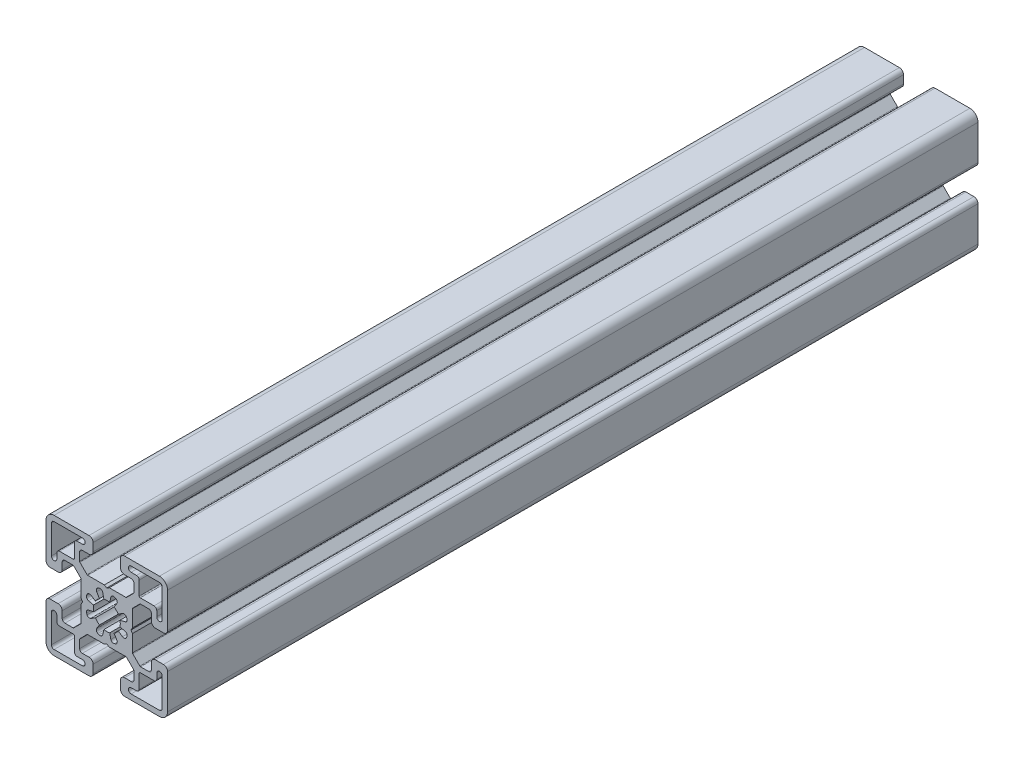
SolidWorks part; units mm, degrees
material "6061 Alloy"
ref_plane "Front Plane" through (0, 0, 0) normal (0, 0, 1) x (1, 0, 0)
ref_plane "Top Plane" through (0, 0, 0) normal (0, 1, 0) x (1, 0, 0)
ref_plane "Right Plane" through (0, 0, 0) normal (1, 0, 0) x (0, 0, -1)
sketch "Sketch1" plane through (0, 0, 0) normal (0, 0, 1) x (1, 0, 0)
  line L0 (-8.0293, -14.4831) -> (-6.0293, -14.4831)
  line L1 (-6.0293, -16.4831) -> (-16.5293, -16.4831)
  line L2 (-17.5293, -15.4831) -> (-17.5293, -4.9831)
  line L3 (-15.5293, -4.9831) -> (-15.5293, -6.9831)
  line L4 (-14.5293, -7.9831) -> (-9.4093, -7.9831)
  line L5 (-9.0293, -8.3631) -> (-9.0293, -13.4831)
  line L6 (-15.5293, 15.0169) -> (-15.5293, 13.0169)
  line L7 (-17.5293, 13.0169) -> (-17.5293, 23.5169)
  line L8 (-16.5293, 24.5169) -> (-6.0293, 24.5169)
  line L9 (-6.0293, 22.5169) -> (-8.0293, 22.5169)
  line L10 (-9.0293, 21.5169) -> (-9.0293, 16.3969)
  line L11 (-9.4093, 16.0169) -> (-14.5293, 16.0169)
  line L12 (14.9707, 16.3969) -> (14.9707, 21.5169)
  line L13 (13.9707, 22.5169) -> (11.9707, 22.5169)
  line L14 (11.9707, 24.5169) -> (22.4707, 24.5169)
  line L15 (23.4707, 23.5169) -> (23.4707, 13.0169)
  line L16 (21.4707, 13.0169) -> (21.4707, 15.0169)
  line L17 (20.4707, 16.0169) -> (15.3507, 16.0169)
  line L18 (8.8137, 0.2931) -> (7.1867, 1.3289)
  line L19 (5.6584, -0.1993) -> (6.6943, -1.826)
  line L20 (4.4692, -2.7478) -> (4.0512, -0.865)
  line L21 (1.8899, -0.8649) -> (1.4721, -2.7476)
  line L22 (-0.7531, -1.8261) -> (0.2827, -0.1991)
  line L23 (-1.2455, 1.3292) -> (-2.8722, 0.2933)
  line L24 (-3.794, 2.5184) -> (-1.9112, 2.9364)
  line L25 (-1.9111, 5.0977) -> (-3.7938, 5.5155)
  line L26 (-2.8723, 7.7407) -> (-1.2453, 6.7049)
  line L27 (0.283, 8.2331) -> (-0.7529, 9.8598)
  line L28 (1.4722, 10.7816) -> (1.8902, 8.8987)
  line L29 (4.0515, 8.8987) -> (4.4693, 10.7814)
  line L30 (6.6945, 9.8599) -> (5.6587, 8.2329)
  line L31 (7.1869, 6.7046) -> (8.8136, 7.7405)
  line L32 (9.7354, 5.5154) -> (7.8526, 5.0973)
  line L33 (7.8525, 2.936) -> (9.7352, 2.5183)
  line L34 (21.4707, -6.9831) -> (21.4707, -4.9831)
  line L35 (23.4707, -4.9831) -> (23.4707, -15.4831)
  line L36 (22.4707, -16.4831) -> (11.9707, -16.4831)
  line L37 (11.9707, -14.4831) -> (13.9707, -14.4831)
  line L38 (14.9707, -13.4831) -> (14.9707, -8.3631)
  line L39 (15.3507, -7.9831) -> (20.4707, -7.9831)
  line L40 (2.0707, -5.4831) -> (2.9707, -4.968)
  line L41 (2.9707, -4.968) -> (3.8707, -5.4831)
  line L42 (3.8707, -5.4831) -> (10.0223, -5.4831)
  line L43 (10.291, -5.5944) -> (12.9094, -8.2128)
  line L44 (13.0207, -8.4815) -> (13.0207, -11.4831)
  line L45 (12.0207, -12.4831) -> (9.5557, -12.4831)
  line L46 (8.0357, -14.0031) -> (8.0357, -16.9631)
  line L47 (9.5557, -18.4831) -> (22.4707, -18.4831)
  line L48 (25.4707, -15.4831) -> (25.4707, -2.5681)
  line L49 (23.9507, -1.0481) -> (20.9907, -1.0481)
  line L50 (19.4707, -2.5681) -> (19.4707, -5.0331)
  line L51 (18.4707, -6.0331) -> (15.4691, -6.0331)
  line L52 (15.2004, -5.9218) -> (12.582, -3.3034)
  line L53 (12.4707, -3.0347) -> (12.4707, 3.1169)
  line L54 (12.4707, 3.1169) -> (11.9511, 4.0169)
  line L55 (11.9511, 4.0169) -> (12.4707, 4.9169)
  line L56 (12.4707, 4.9169) -> (12.4707, 11.0685)
  line L57 (12.582, 11.3372) -> (15.2004, 13.9556)
  line L58 (15.4691, 14.0669) -> (18.4707, 14.0669)
  line L59 (19.4707, 13.0669) -> (19.4707, 10.6019)
  line L60 (20.9907, 9.0819) -> (23.9507, 9.0819)
  line L61 (25.4707, 10.6019) -> (25.4707, 23.5169)
  line L62 (22.4707, 26.5169) -> (9.5557, 26.5169)
  line L63 (8.0357, 24.9969) -> (8.0357, 22.0369)
  line L64 (9.5557, 20.5169) -> (12.0207, 20.5169)
  line L65 (13.0207, 19.5169) -> (13.0207, 16.5153)
  line L66 (12.9094, 16.2466) -> (10.291, 13.6282)
  line L67 (10.0223, 13.5169) -> (3.8707, 13.5169)
  line L68 (3.8707, 13.5169) -> (2.9707, 13.0017)
  line L69 (2.9707, 13.0017) -> (2.0707, 13.5169)
  line L70 (2.0707, 13.5169) -> (-4.0809, 13.5169)
  line L71 (-4.3496, 13.6282) -> (-6.968, 16.2466)
  line L72 (-7.0793, 16.5153) -> (-7.0793, 19.5169)
  line L73 (-6.0793, 20.5169) -> (-3.6143, 20.5169)
  line L74 (-2.0943, 22.0369) -> (-2.0943, 24.9969)
  line L75 (-3.6143, 26.5169) -> (-16.5293, 26.5169)
  line L76 (-19.5293, 23.5169) -> (-19.5293, 10.6019)
  line L77 (-18.0093, 9.0819) -> (-15.0493, 9.0819)
  line L78 (-13.5293, 10.6019) -> (-13.5293, 13.0669)
  line L79 (-12.5293, 14.0669) -> (-9.5277, 14.0669)
  line L80 (-9.259, 13.9556) -> (-6.6406, 11.3372)
  line L81 (-6.5293, 11.0685) -> (-6.5293, 4.9169)
  line L82 (-6.5293, 4.9169) -> (-6.0097, 4.0169)
  line L83 (-6.0097, 4.0169) -> (-6.5293, 3.1169)
  line L84 (-6.5293, 3.1169) -> (-6.5293, -3.0347)
  line L85 (-6.6406, -3.3034) -> (-9.259, -5.9218)
  line L86 (-9.5277, -6.0331) -> (-12.5293, -6.0331)
  line L87 (-13.5293, -5.0331) -> (-13.5293, -2.5681)
  line L88 (-15.0493, -1.0481) -> (-18.0093, -1.0481)
  line L89 (-19.5293, -2.5681) -> (-19.5293, -15.4831)
  line L90 (-16.5293, -18.4831) -> (-3.6143, -18.4831)
  line L91 (-2.0943, -16.9631) -> (-2.0943, -14.0031)
  line L92 (-3.6143, -12.4831) -> (-6.0793, -12.4831)
  line L93 (-7.0793, -11.4831) -> (-7.0793, -8.4815)
  line L94 (-6.968, -8.2128) -> (-4.3496, -5.5944)
  line L95 (-4.0809, -5.4831) -> (2.0707, -5.4831)
  arc A0 (-9.0293, -13.4831) -> (-8.0293, -14.4831) centre (-8.0293, -13.4831) ccw
  arc A1 (-6.0293, -16.4831) -> (-6.0293, -14.4831) centre (-6.0293, -15.4831) ccw
  arc A2 (-17.5293, -15.4831) -> (-16.5293, -16.4831) centre (-16.5293, -15.4831) ccw
  arc A3 (-15.5293, -4.9831) -> (-17.5293, -4.9831) centre (-16.5293, -4.9831) ccw
  arc A4 (-15.5293, -6.9831) -> (-14.5293, -7.9831) centre (-14.5293, -6.9831) ccw
  arc A5 (-9.0293, -8.3631) -> (-9.4093, -7.9831) centre (-9.4093, -8.3631) ccw
  arc A6 (-14.5293, 16.0169) -> (-15.5293, 15.0169) centre (-14.5293, 15.0169) ccw
  arc A7 (-17.5293, 13.0169) -> (-15.5293, 13.0169) centre (-16.5293, 13.0169) ccw
  arc A8 (-16.5293, 24.5169) -> (-17.5293, 23.5169) centre (-16.5293, 23.5169) ccw
  arc A9 (-6.0293, 22.5169) -> (-6.0293, 24.5169) centre (-6.0293, 23.5169) ccw
  arc A10 (-8.0293, 22.5169) -> (-9.0293, 21.5169) centre (-8.0293, 21.5169) ccw
  arc A11 (-9.4093, 16.0169) -> (-9.0293, 16.3969) centre (-9.4093, 16.3969) ccw
  arc A12 (14.9707, 16.3969) -> (15.3507, 16.0169) centre (15.3507, 16.3969) ccw
  arc A13 (14.9707, 21.5169) -> (13.9707, 22.5169) centre (13.9707, 21.5169) ccw
  arc A14 (11.9707, 24.5169) -> (11.9707, 22.5169) centre (11.9707, 23.5169) ccw
  arc A15 (23.4707, 23.5169) -> (22.4707, 24.5169) centre (22.4707, 23.5169) ccw
  arc A16 (21.4707, 13.0169) -> (23.4707, 13.0169) centre (22.4707, 13.0169) ccw
  arc A17 (21.4707, 15.0169) -> (20.4707, 16.0169) centre (20.4707, 15.0169) ccw
  arc A18 (10.2621, 0.7252) -> (10.454, 1.1885) centre (2.9707, 4.0169) ccw
  arc A19 (8.8137, 0.2931) -> (10.2621, 0.7252) centre (9.3507, 1.1367) ccw
  arc A20 (5.6584, -0.1993) -> (7.1867, 1.3289) centre (2.9707, 4.0169) ccw
  arc A21 (6.2622, -3.2746) -> (6.6943, -1.826) centre (5.8508, -2.3632) ccw
  arc A22 (5.799, -3.4665) -> (6.2622, -3.2746) centre (2.9707, 4.0169) ccw
  arc A23 (4.4692, -2.7478) -> (5.799, -3.4665) centre (5.4454, -2.5311) ccw
  arc A24 (1.8899, -0.8649) -> (4.0512, -0.865) centre (2.9707, 4.0169) ccw
  arc A25 (0.1423, -3.4664) -> (1.4721, -2.7476) centre (0.4958, -2.531) ccw
  arc A26 (-0.321, -3.2745) -> (0.1423, -3.4664) centre (2.9707, 4.0169) ccw
  arc A27 (-0.7531, -1.8261) -> (-0.321, -3.2745) centre (0.0905, -2.3631) ccw
  arc A28 (-1.2455, 1.3292) -> (0.2827, -0.1991) centre (2.9707, 4.0169) ccw
  arc A29 (-4.3208, 0.7254) -> (-2.8722, 0.2933) centre (-3.4094, 1.1368) ccw
  arc A30 (-4.5127, 1.1886) -> (-4.3208, 0.7254) centre (2.9707, 4.0169) ccw
  arc A31 (-3.794, 2.5184) -> (-4.5127, 1.1886) centre (-3.5773, 1.5422) ccw
  arc A32 (-1.9111, 5.0977) -> (-1.9112, 2.9364) centre (2.9707, 4.0169) ccw
  arc A33 (-4.5126, 6.8453) -> (-3.7938, 5.5155) centre (-3.5772, 6.4917) ccw
  arc A34 (-4.3207, 7.3085) -> (-4.5126, 6.8453) centre (2.9707, 4.0169) ccw
  arc A35 (-2.8723, 7.7407) -> (-4.3207, 7.3085) centre (-3.4093, 6.8971) ccw
  arc A36 (0.283, 8.2331) -> (-1.2453, 6.7049) centre (2.9707, 4.0169) ccw
  arc A37 (-0.3208, 11.3084) -> (-0.7529, 9.8598) centre (0.0906, 10.3969) ccw
  arc A38 (0.1424, 11.5003) -> (-0.3208, 11.3084) centre (2.9707, 4.0169) ccw
  arc A39 (1.4722, 10.7816) -> (0.1424, 11.5003) centre (0.496, 10.5648) ccw
  arc A40 (4.0515, 8.8987) -> (1.8902, 8.8987) centre (2.9707, 4.0169) ccw
  arc A41 (5.7991, 11.5002) -> (4.4693, 10.7814) centre (5.4456, 10.5648) ccw
  arc A42 (6.2624, 11.3083) -> (5.7991, 11.5002) centre (2.9707, 4.0169) ccw
  arc A43 (6.6945, 9.8599) -> (6.2624, 11.3083) centre (5.8509, 10.3969) ccw
  arc A44 (7.1869, 6.7046) -> (5.6587, 8.2329) centre (2.9707, 4.0169) ccw
  arc A45 (10.2622, 7.3084) -> (8.8136, 7.7405) centre (9.3508, 6.897) ccw
  arc A46 (10.4541, 6.8451) -> (10.2622, 7.3084) centre (2.9707, 4.0169) ccw
  arc A47 (9.7354, 5.5154) -> (10.4541, 6.8451) centre (9.5187, 6.4916) ccw
  arc A48 (7.8525, 2.936) -> (7.8526, 5.0973) centre (2.9707, 4.0169) ccw
  arc A49 (10.454, 1.1885) -> (9.7352, 2.5183) centre (9.5186, 1.542) ccw
  arc A50 (20.4707, -7.9831) -> (21.4707, -6.9831) centre (20.4707, -6.9831) ccw
  arc A51 (23.4707, -4.9831) -> (21.4707, -4.9831) centre (22.4707, -4.9831) ccw
  arc A52 (22.4707, -16.4831) -> (23.4707, -15.4831) centre (22.4707, -15.4831) ccw
  arc A53 (11.9707, -14.4831) -> (11.9707, -16.4831) centre (11.9707, -15.4831) ccw
  arc A54 (13.9707, -14.4831) -> (14.9707, -13.4831) centre (13.9707, -13.4831) ccw
  arc A55 (15.3507, -7.9831) -> (14.9707, -8.3631) centre (15.3507, -8.3631) ccw
  arc A56 (10.291, -5.5944) -> (10.0223, -5.4831) centre (10.0223, -5.8631) ccw
  arc A57 (13.0207, -8.4815) -> (12.9094, -8.2128) centre (12.6407, -8.4815) ccw
  arc A58 (12.0207, -12.4831) -> (13.0207, -11.4831) centre (12.0207, -11.4831) ccw
  arc A59 (9.5557, -12.4831) -> (8.0357, -14.0031) centre (9.5557, -14.0031) ccw
  arc A60 (8.0357, -16.9631) -> (9.5557, -18.4831) centre (9.5557, -16.9631) ccw
  arc A61 (22.4707, -18.4831) -> (25.4707, -15.4831) centre (22.4707, -15.4831) ccw
  arc A62 (25.4707, -2.5681) -> (23.9507, -1.0481) centre (23.9507, -2.5681) ccw
  arc A63 (20.9907, -1.0481) -> (19.4707, -2.5681) centre (20.9907, -2.5681) ccw
  arc A64 (18.4707, -6.0331) -> (19.4707, -5.0331) centre (18.4707, -5.0331) ccw
  arc A65 (15.2004, -5.9218) -> (15.4691, -6.0331) centre (15.4691, -5.6531) ccw
  arc A66 (12.4707, -3.0347) -> (12.582, -3.3034) centre (12.8507, -3.0347) ccw
  arc A67 (12.582, 11.3372) -> (12.4707, 11.0685) centre (12.8507, 11.0685) ccw
  arc A68 (15.4691, 14.0669) -> (15.2004, 13.9556) centre (15.4691, 13.6869) ccw
  arc A69 (19.4707, 13.0669) -> (18.4707, 14.0669) centre (18.4707, 13.0669) ccw
  arc A70 (19.4707, 10.6019) -> (20.9907, 9.0819) centre (20.9907, 10.6019) ccw
  arc A71 (23.9507, 9.0819) -> (25.4707, 10.6019) centre (23.9507, 10.6019) ccw
  arc A72 (25.4707, 23.5169) -> (22.4707, 26.5169) centre (22.4707, 23.5169) ccw
  arc A73 (9.5557, 26.5169) -> (8.0357, 24.9969) centre (9.5557, 24.9969) ccw
  arc A74 (8.0357, 22.0369) -> (9.5557, 20.5169) centre (9.5557, 22.0369) ccw
  arc A75 (13.0207, 19.5169) -> (12.0207, 20.5169) centre (12.0207, 19.5169) ccw
  arc A76 (12.9094, 16.2466) -> (13.0207, 16.5153) centre (12.6407, 16.5153) ccw
  arc A77 (10.0223, 13.5169) -> (10.291, 13.6282) centre (10.0223, 13.8969) ccw
  arc A78 (-4.3496, 13.6282) -> (-4.0809, 13.5169) centre (-4.0809, 13.8969) ccw
  arc A79 (-7.0793, 16.5153) -> (-6.968, 16.2466) centre (-6.6993, 16.5153) ccw
  arc A80 (-6.0793, 20.5169) -> (-7.0793, 19.5169) centre (-6.0793, 19.5169) ccw
  arc A81 (-3.6143, 20.5169) -> (-2.0943, 22.0369) centre (-3.6143, 22.0369) ccw
  arc A82 (-2.0943, 24.9969) -> (-3.6143, 26.5169) centre (-3.6143, 24.9969) ccw
  arc A83 (-16.5293, 26.5169) -> (-19.5293, 23.5169) centre (-16.5293, 23.5169) ccw
  arc A84 (-19.5293, 10.6019) -> (-18.0093, 9.0819) centre (-18.0093, 10.6019) ccw
  arc A85 (-15.0493, 9.0819) -> (-13.5293, 10.6019) centre (-15.0493, 10.6019) ccw
  arc A86 (-12.5293, 14.0669) -> (-13.5293, 13.0669) centre (-12.5293, 13.0669) ccw
  arc A87 (-9.259, 13.9556) -> (-9.5277, 14.0669) centre (-9.5277, 13.6869) ccw
  arc A88 (-6.5293, 11.0685) -> (-6.6406, 11.3372) centre (-6.9093, 11.0685) ccw
  arc A89 (-6.6406, -3.3034) -> (-6.5293, -3.0347) centre (-6.9093, -3.0347) ccw
  arc A90 (-9.5277, -6.0331) -> (-9.259, -5.9218) centre (-9.5277, -5.6531) ccw
  arc A91 (-13.5293, -5.0331) -> (-12.5293, -6.0331) centre (-12.5293, -5.0331) ccw
  arc A92 (-13.5293, -2.5681) -> (-15.0493, -1.0481) centre (-15.0493, -2.5681) ccw
  arc A93 (-18.0093, -1.0481) -> (-19.5293, -2.5681) centre (-18.0093, -2.5681) ccw
  arc A94 (-19.5293, -15.4831) -> (-16.5293, -18.4831) centre (-16.5293, -15.4831) ccw
  arc A95 (-3.6143, -18.4831) -> (-2.0943, -16.9631) centre (-3.6143, -16.9631) ccw
  arc A96 (-2.0943, -14.0031) -> (-3.6143, -12.4831) centre (-3.6143, -14.0031) ccw
  arc A97 (-7.0793, -11.4831) -> (-6.0793, -12.4831) centre (-6.0793, -11.4831) ccw
  arc A98 (-6.968, -8.2128) -> (-7.0793, -8.4815) centre (-6.6993, -8.4815) ccw
  arc A99 (-4.0809, -5.4831) -> (-4.3496, -5.5944) centre (-4.0809, -5.8631) ccw
extrude "Extrude1" add sketch "Sketch1" along normal blind 300
